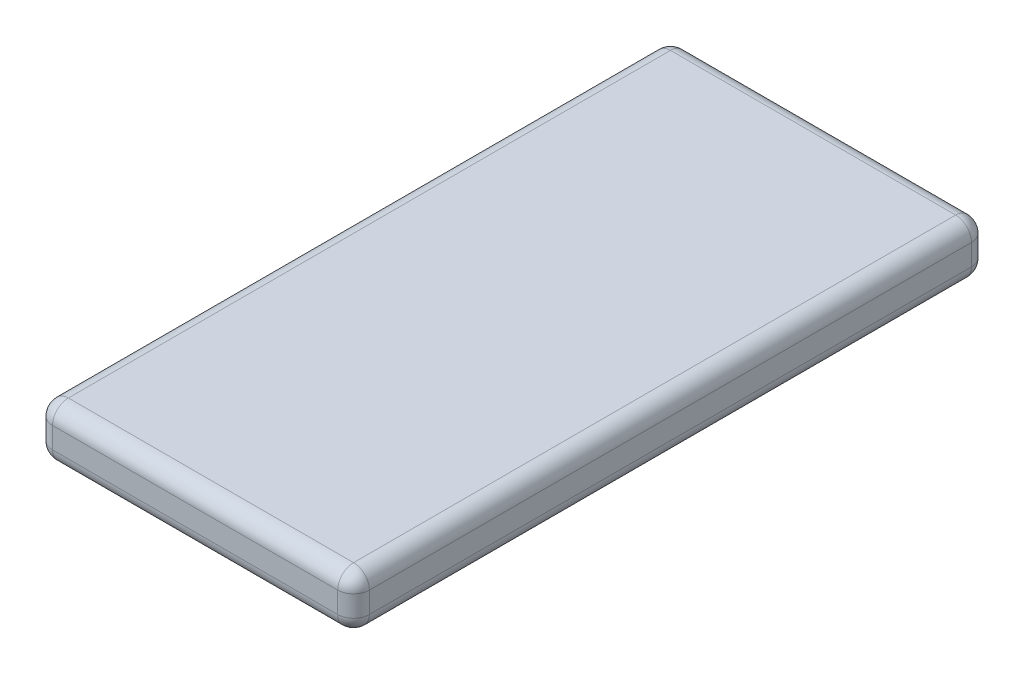
SolidWorks part; units mm, degrees
ref_plane "Front Plane" through (0, 0, 0) normal (0, 0, 1) x (1, 0, 0)
ref_plane "Top Plane" through (0, 0, 0) normal (0, 1, 0) x (1, 0, 0)
ref_plane "Right Plane" through (0, 0, 0) normal (1, 0, 0) x (0, 0, -1)
sketch "Sketch2" plane through (0, 0, 0) normal (0, 1, 0) x (1, 0, 0)
  line L1 (300, 600) -> (-300, 600)
  line L2 (300, 600) -> (300, -600)
  line L3 (300, -600) -> (-300, -600)
  line L4 (-300, 600) -> (-300, -600)
  line L5 (300, 600) -> (-300, -600) construction
  line L6 (300, -600) -> (-300, 600) construction
  point P0 (0, 0)
  dimension "D1" = 600
  dimension "D2" = 1200
extrude "Boss-Extrude1" add sketch "Sketch2" along normal blind 100
fillet "Fillet1" radius 30 12 edges at (0, 0, 600) (-300, 50, 600) (-300, 0, 0) (-300, 50, -600) (0, 0, -600) (300, 50, 600) (300, 50, -600) (300, 0, 0) (0, 100, -600) (300, 100, 0) (0, 100, 600) (-300, 100, 0)
